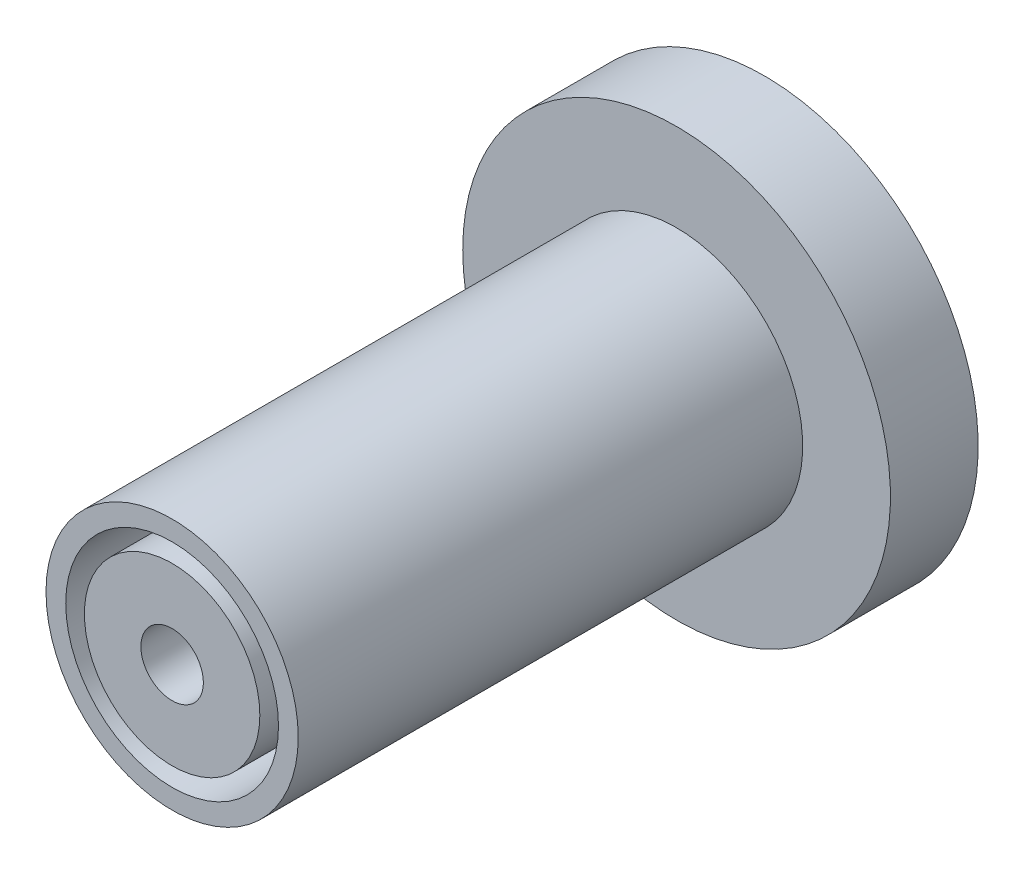
SolidWorks part; units mm, degrees
ref_plane "Front Plane" through (0, 0, 0) normal (0, 0, 1) x (1, 0, 0)
ref_plane "Top Plane" through (0, 0, 0) normal (0, 1, 0) x (1, 0, 0)
ref_plane "Right Plane" through (0, 0, 0) normal (1, 0, 0) x (0, 0, -1)
sketch "Sketch2" plane through (0, 0, 0) normal (0, 0, 1) x (1, 0, 0)
  circle A0 centre (0, 0) radius 5.75
  dimension "D1" = 11.5
extrude "Boss-Extrude1" add sketch "Sketch2" along normal blind 6
sketch "Sketch3" plane through (0, 0, 6) normal (0, 0, 1) x (1, 0, 0)
  circle A0 centre (0, 0) radius 4.85
  dimension "D1" = 9.7
extrude "Cut-Extrude1" cut sketch "Sketch3" against normal blind 4
sketch "Sketch4" plane through (0, 0, 0) normal (0, 0, -1) x (-1, 0, 0)
  circle A0 centre (0, 0) radius 4.75
  dimension "D1" = 9.5
extrude "Boss-Extrude2" add sketch "Sketch4" along normal blind 21
sketch "Sketch5" plane through (0, 0, -21) normal (0, 0, -1) x (-1, 0, 0)
  line L0 (-4.75, 0) -> (4.75, 0) construction
  line L1 (-3, 1.8802) -> (-3, -1.9198)
  line L2 (3, 1.8802) -> (3, -1.9198)
  circle A3 centre (0, 0) radius 4.75 construction
  circle A4 centre (0, 0) radius 4.75 construction
  arc A5 (-3, 1.8802) -> (3, 1.8802) centre (0, 0) cw
  arc A6 (-3, -1.9198) -> (3, -1.9198) centre (0, 0) ccw
  point P8 (2.95, -1.8727)
  point P11 (0, 0)
  point P12 (0, 0)
  point P13 (0, 0)
  point P17 (2.95, 1.7988)
  dimension "D1" = 3.8
  dimension "D2" = 3.8
  dimension "D3" = 3
  dimension "D4" = 3
extrude "Cut-Extrude2" cut sketch "Sketch5" against normal blind 21
ref_plane "Plane1" through (0, 0, 2.8) normal (0, 0, 1) x (1, 0, 0)
sketch "Sketch7" plane through (0, 0, 2.8) normal (0, 0, 1) x (1, 0, 0)
  circle A0 centre (0, 0) radius 4
  dimension "D1" = 8
extrude "Boss-Extrude3" add sketch "Sketch7" along normal blind 3.2 separate body
sketch "Sketch8" plane through (0, 0, 6) normal (0, 0, 1) x (1, 0, 0)
  circle A0 centre (0, 0) radius 1.425
  dimension "D1" = 2.85
extrude "Cut-Extrude3" cut sketch "Sketch8" against normal blind 2.8
sketch "Sketch11" plane through (0, 0, -21) normal (0, 0, -1) x (-1, 0, 0)
  circle A0 centre (0, 0) radius 4.75
  circle A1 centre (0, 0) radius 5.75
  dimension "D1" = 9.5
  dimension "D2" = 11.5
extrude "Boss-Extrude5" add sketch "Sketch11" against normal blind 21
sketch "Sketch12" plane through (0, 0, -21) normal (0, 0, -1) x (-1, 0, 0)
  circle A0 centre (0, 0) radius 5.75
  circle A1 centre (0, 0) radius 9.75
  dimension "D1" = 11.5
  dimension "D2" = 19.5
extrude "Boss-Extrude6" add sketch "Sketch12" against normal blind 4
